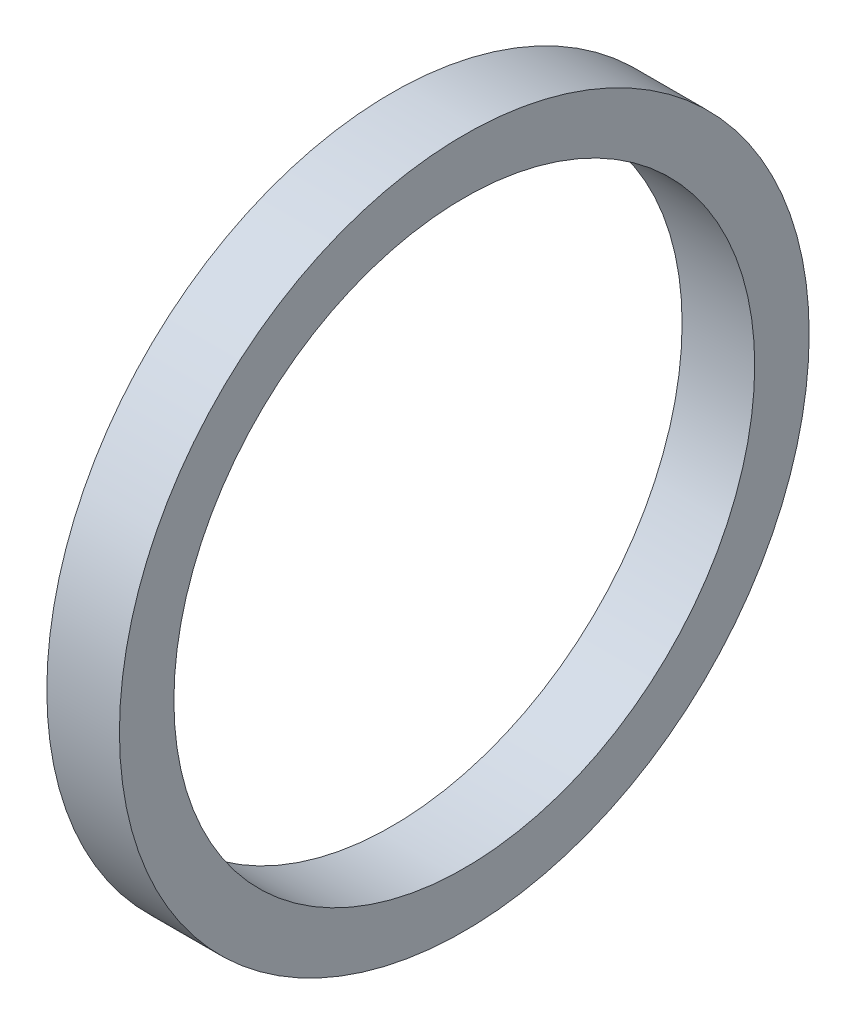
SolidWorks part; units mm, degrees
ref_plane "Front Plane" through (0, 0, 0) normal (0, 0, 1) x (1, 0, 0)
ref_plane "Top Plane" through (0, 0, 0) normal (0, 1, 0) x (1, 0, 0)
ref_plane "Right Plane" through (0, 0, 0) normal (1, 0, 0) x (0, 0, -1)
sketch "Sketch1" plane through (0, 0, 0) normal (1, 0, 0) x (0, 0, -1)
  circle A0 centre (0, 0) radius 4
  circle A1 centre (0, 0) radius 4.75
  dimension "D1" = 8
  dimension "D2" = 9.5
extrude "Boss-Extrude1" add sketch "Sketch1" along normal blind 1
